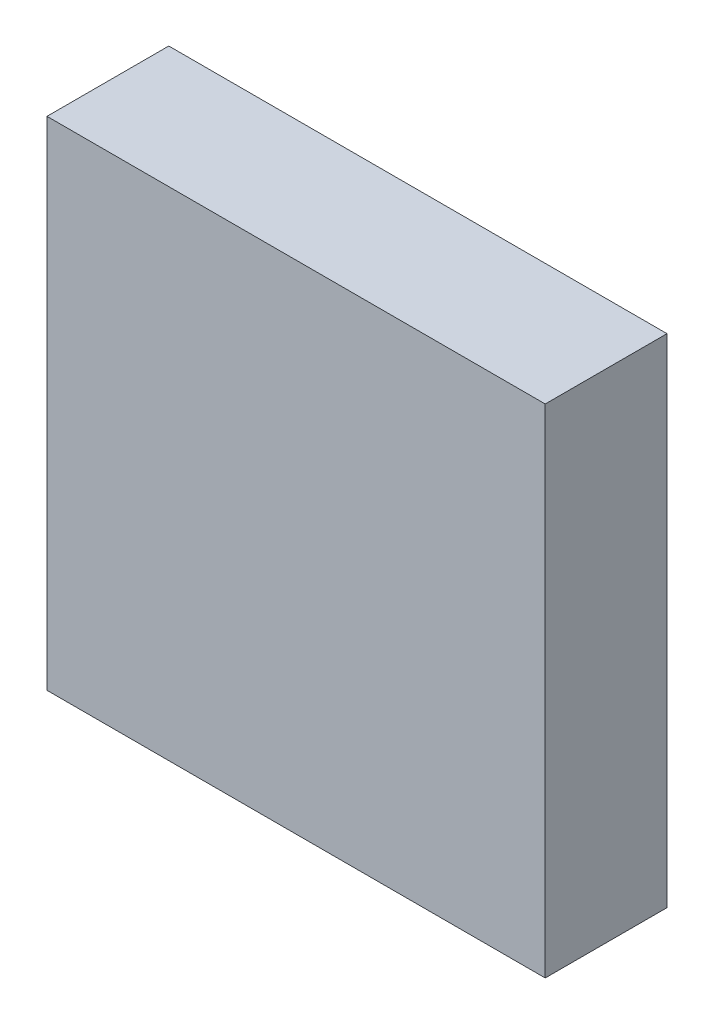
SolidWorks part; units mm, degrees
ref_plane "Ebene vorne" through (0, 0, 0) normal (0, 0, 1) x (1, 0, 0)
ref_plane "Ebene oben" through (0, 0, 0) normal (0, 1, 0) x (1, 0, 0)
ref_plane "Ebene rechts" through (0, 0, 0) normal (1, 0, 0) x (0, 0, -1)
sketch "Skizze1" plane through (0, 0, 0) normal (0, 0, 1) x (1, 0, 0)
  line L5 (-22.5, 22.45) -> (22.5, 22.45)
  line L6 (-22.5, 22.45) -> (-22.5, -22.45)
  line L7 (-22.5, -22.45) -> (22.5, -22.45)
  line L8 (22.5, 22.45) -> (22.5, -22.45)
extrude "Aufsatz-Linear austragen1" add sketch "Skizze1" along normal blind 11
sketch "Skizze3" plane through (0, 0, 0) normal (0, 0, -1) x (-1, 0, 0)
  circle A0 centre (0, 0) radius 15.75
  dimension "D1" = 31.5
extrude "Schnitt-Linear austragen1" cut sketch "Skizze3" against normal blind 10
sketch "Skizze7" plane through (0, 0, 0) normal (0, 0, -1) x (-1, 0, 0)
  circle A0 centre (0, 0) radius 11.5
  dimension "D1" = 23
extrude "Aufsatz-Linear austragen3" add sketch "Skizze7" against normal blind 10
sketch "Skizze8" plane through (0, 0, 0) normal (0, 0, -1) x (-1, 0, 0)
  circle A0 centre (0, 0) radius 11
  dimension "D1" = 22
extrude "Schnitt-Linear austragen4" cut sketch "Skizze8" against normal blind 7
